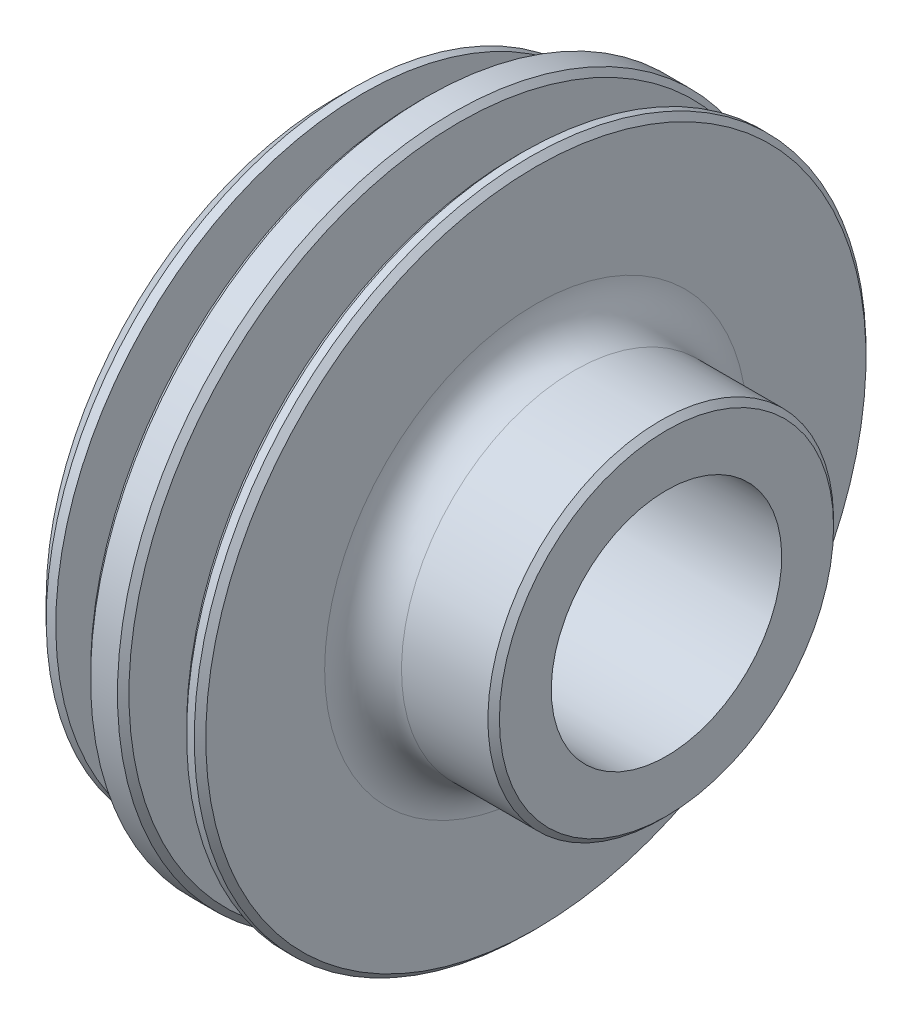
SolidWorks part; units mm, degrees
ref_plane "Plan de face" through (0, 0, 0) normal (0, 0, 1) x (1, 0, 0)
ref_plane "Plan de dessus" through (0, 0, 0) normal (0, 1, 0) x (1, 0, 0)
ref_plane "Plan de droite" through (0, 0, 0) normal (1, 0, 0) x (0, 0, -1)
sketch "Esquisse1" plane through (0, 0, 0) normal (0, 0, 1) x (1, 0, 0)
  line L0 (0, 0) -> (0, 8.5)
  line L1 (0, 8.5) -> (2.5, 11)
  line L4 (4, 16) -> (4, 12.8265)
  line L5 (4, 12.8265) -> (4, 11.5)
  line L6 (4, 11.5) -> (7, 11.5)
  line L7 (7, 11.5) -> (7, 17.1896)
  line L8 (7.3, 17.4896) -> (8.7, 17.4896)
  line L9 (9, 17.1896) -> (9, 12)
  line L10 (9, 12) -> (12, 12)
  line L11 (12, 12) -> (12, 17.1896)
  line L12 (12.3, 17.4896) -> (12.7, 17.4896)
  line L13 (13, 17.1896) -> (13, 11)
  line L14 (15, 9) -> (19.5, 9)
  line L18 (7, 17.1896) -> (7.3, 17.4896)
  line L19 (8.7, 17.4896) -> (9, 17.1896)
  line L20 (12, 17.1896) -> (12.3, 17.4896)
  line L21 (12.7, 17.4896) -> (13, 17.1896)
  line L22 (19.5, 9) -> (19.8, 8.7)
  line L23 (2.5, 11) -> (2.5, 0) construction
  line L24 (19.5, 9) -> (19.8, 9) construction
  line L29 (19.8, 9) -> (19.8, 8.7) construction
  line L30 (13, 9) -> (17.25, 9) construction
  line L31 (4, 11.5) -> (3.5, 11.5) construction
  line L32 (3.5, 11.5) -> (3.5, 16) construction
  line L33 (4, 16) -> (3.5, 16)
  line L34 (2.5, 11) -> (2.5, 15)
  line L35 (2.5, 15) -> (3.5, 16)
  line L36 (4, 16) -> (2.5, 16) construction
  line L37 (19.8, 6) -> (-0.1447, 6) construction
  line L38 (19.8, 8.7) -> (19.8, 6)
  line L39 (7.8, 6) -> (7.8, 0)
  line L40 (7.8, 6) -> (19.8, 6)
  line L41 (7.8, 0) -> (0, 0)
  arc A0 (13, 11) -> (15, 9) centre (15, 11) ccw
  point P10 (7, 17.4896)
  point P11 (9, 17.4896)
  point P14 (12, 17.4896)
  point P15 (13, 17.4896)
  point P17 (19.8, 9)
  dimension "D25" = 2
  dimension "D1" = 8.5
  dimension "D3" = 45
  dimension "D4" = 0.5
  dimension "D5" = 45
  dimension "D6" = 3
  dimension "D7" = 2
  dimension "D8" = 0.3
  dimension "D9" = 45
  dimension "D10" = 0.3
  dimension "D11" = 45
  dimension "D12" = 1
  dimension "D13" = 0.3
  dimension "D14" = 45
  dimension "D15" = 0.3
  dimension "D16" = 45
  dimension "D17" = 0.3
  dimension "D18" = 45
  dimension "D19" = 2.5
  dimension "D23" = 3
  dimension "D24" = 6.5
  dimension "D28" = 1.5
revolve "Révolution1" add sketch "Esquisse1" angle 360 about L41
